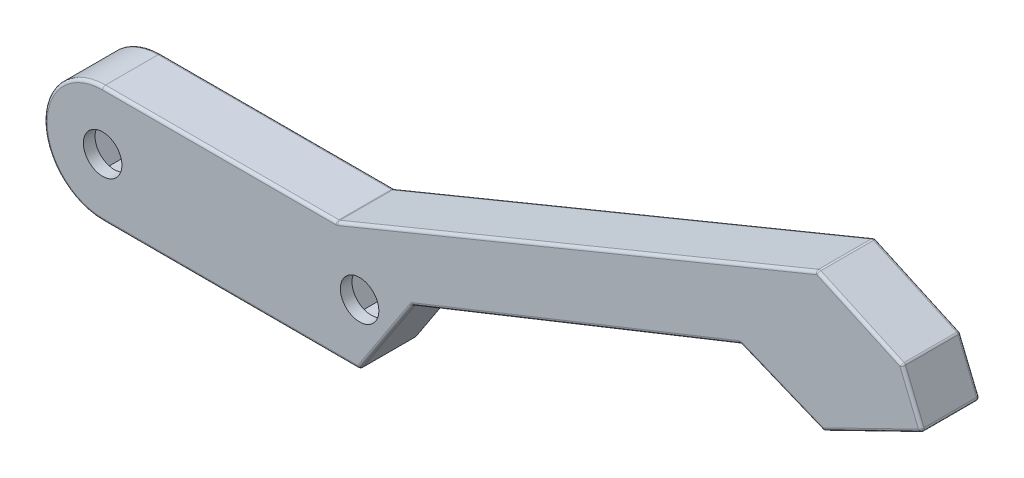
SolidWorks part; units mm, degrees
ref_plane "Front Plane" through (0, 0, 0) normal (0, 0, 1) x (1, 0, 0)
ref_plane "Top Plane" through (0, 0, 0) normal (0, 1, 0) x (1, 0, 0)
ref_plane "Right Plane" through (0, 0, 0) normal (1, 0, 0) x (0, 0, -1)
sketch "Sketch1" plane through (0, 0, 0) normal (0, 0, 1) x (1, 0, 0)
  line L0 (-25.2186, -6.4645) -> (-3.2186, -6.4645) construction
  line L1 (-25.2186, -1.4645) -> (-3.2186, -1.4645)
  line L2 (-25.2186, -11.4645) -> (-3.2186, -11.4645)
  line L3 (-5.1686, -1.4645) -> (-1.2272, -11.0508) construction
  line L4 (-5.1686, -1.4645) -> (41.0753, 17.5487) construction
  line L5 (-1.2272, -11.0508) -> (45.0167, 7.9624) construction
  line L6 (41.0753, 17.5487) -> (45.0167, 7.9624) construction
  line L7 (-5.1686, -1.4645) -> (35.9884, 15.4572)
  line L8 (35.9884, 15.4572) -> (43.3055, 12.1243)
  line L9 (43.3055, 12.1243) -> (45.0167, 7.9624)
  line L10 (35.7679, 4.1597) -> (29.4506, 6.7428)
  line L11 (29.4506, 6.7428) -> (1.3656, -4.4682)
  line L12 (35.7679, 4.1597) -> (45.0167, 7.9624) construction
  line L13 (35.7679, 4.1597) -> (36.5638, 3.8396)
  line L23 (36.5638, 3.8396) -> (45.0167, 7.9624)
  line L24 (1.3656, -4.4682) -> (-3.2186, -11.4645)
  arc A0 (-25.2186, -1.4645) -> (-25.2186, -11.4645) centre (-25.2186, -6.4645) ccw
  arc A1 (-3.2186, -11.4645) -> (-3.2186, -1.4645) centre (-3.2186, -6.4645) ccw
  circle A2 centre (-25.2186, -6.4645) radius 1.65
  circle A3 centre (-3.1979, -6.2576) radius 1.65
  point P2 (-14.2186, -6.4645)
  dimension "D11" = 3.3
  dimension "D1" = 10
  dimension "D2" = 22
  dimension "D3" = 157.65
  dimension "D4" = 1.95
  dimension "D5" = 5.5
  dimension "D6" = 4.5
  dimension "D7" = 10
  dimension "D8" = 136
  dimension "D9" = 50
  dimension "D10" = 30.24
extrude "Boss-Extrude1" add sketch "Sketch1" along normal blind 5
fillet "Fillet2" radius 0.25 31 edges at (-14.2186, -11.4645, 0) (-14.2186, -11.4645, 5) (-30.2186, -6.4645, 0) (-30.2186, -6.4645, 5) (32.6093, 5.4513, 0) (32.6093, 5.4513, 5) (-15.1936, -1.4645, 0) (-15.1936, -1.4645, 5) (45.0167, 7.9624, 2.5) (44.1611, 10.0434, 0) (44.1611, 10.0434, 5) (43.3055, 12.1243, 2.5) (39.647, 13.7908, 0) (39.647, 13.7908, 5) (15.4081, 1.1373, 0) (15.4081, 1.1373, 5) (29.4506, 6.7428, 2.5) (-3.2186, -11.4645, 2.5) (-0.9265, -7.9663, 0) (-0.9265, -7.9663, 5) (1.3656, -4.4682, 2.5) (35.9884, 15.4572, 2.5) (15.4099, 6.9964, 0) (15.4099, 6.9964, 5) (-5.1686, -1.4645, 2.5) (36.1659, 3.9997, 0) (36.1659, 3.9997, 5) (36.5638, 3.8396, 2.5) (40.7903, 5.901, 0) (40.7903, 5.901, 5) (35.7679, 4.1597, 2.5)
sketch "Sketch2" plane through (0, 0, 0) normal (0, 0, 1) x (1, 0, 0)
  line L1 (-23.6309, -9.2145) -> (-22.0432, -6.4645)
  line L2 (-22.0432, -6.4645) -> (-23.6309, -3.7145)
  line L3 (-23.6309, -3.7145) -> (-26.8063, -3.7145)
  line L4 (-26.8063, -3.7145) -> (-28.3941, -6.4645)
  line L5 (-28.3941, -6.4645) -> (-26.8063, -9.2145)
  line L6 (-26.8063, -9.2145) -> (-23.6309, -9.2145)
  line L8 (-25.2186, -11.2145) -> (-3.3537, -11.2145) construction
  line L9 (-3.3537, -11.2145) -> (1.1132, -4.3971) construction
  line L10 (-0.0276, -6.4368) -> (-1.4576, -3.6016)
  line L11 (-1.4576, -3.6016) -> (-4.628, -3.4224)
  line L12 (-4.628, -3.4224) -> (-6.3683, -6.0785)
  line L13 (-6.3683, -6.0785) -> (-4.9383, -8.9137)
  line L14 (-4.9383, -8.9137) -> (-1.7679, -9.0928)
  line L15 (-1.7679, -9.0928) -> (-0.0276, -6.4368)
  circle A0 centre (-25.2186, -6.4645) radius 2.75 construction
  circle A1 centre (-3.1979, -6.2576) radius 2.75 construction
  dimension "D1" = 5.5
  dimension "D2" = 5.5
extrude "Cut-Extrude1" cut sketch "Sketch2" along normal blind 4
